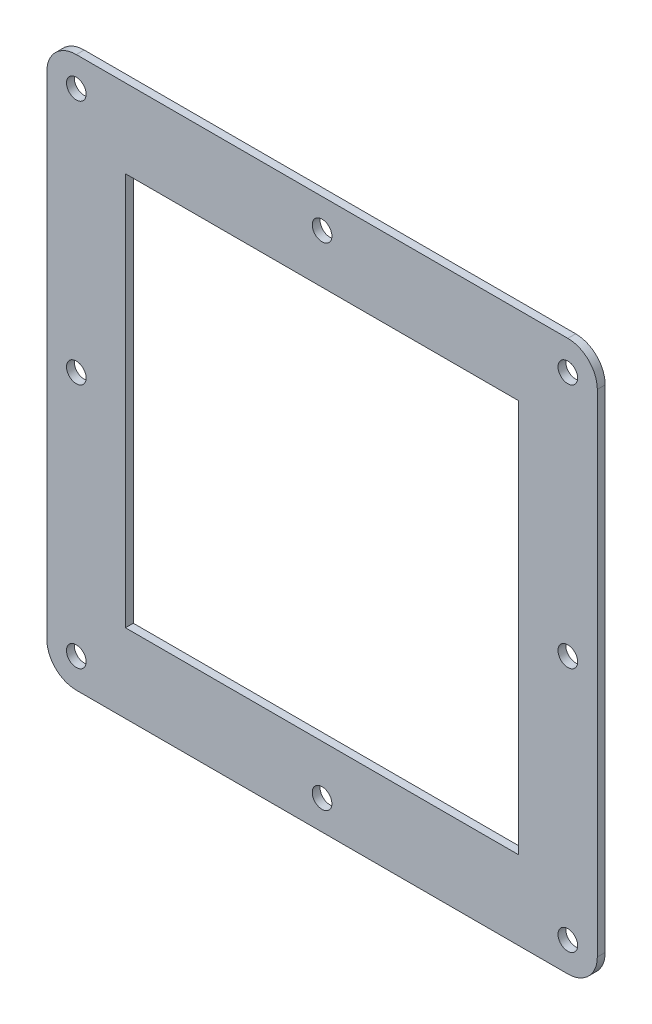
SolidWorks part; units mm, degrees
ref_plane "Front Plane" through (0, 0, 0) normal (0, 0, 1) x (1, 0, 0)
ref_plane "Top Plane" through (0, 0, 0) normal (0, 1, 0) x (1, 0, 0)
ref_plane "Right Plane" through (0, 0, 0) normal (1, 0, 0) x (0, 0, -1)
sketch "Sketch2" plane through (0, 0, 0) normal (0, 0, 1) x (1, 0, 0)
  line L0 (-125, 125) -> (125, 125) construction
  line L1 (-125, 140) -> (125, 140)
  line L2 (-140, 125) -> (-140, -125)
  line L3 (-125, -140) -> (125, -140)
  line L4 (140, 125) -> (140, -125)
  line L5 (-140, 140) -> (140, -140) construction
  line L6 (-140, -140) -> (140, 140) construction
  line L7 (125, 125) -> (125, -125) construction
  line L8 (125, -125) -> (-125, -125) construction
  line L9 (-125, -125) -> (-125, 125) construction
  arc A0 (-140, -125) -> (-125, -140) centre (-125, -125) ccw
  arc A1 (125, -140) -> (140, -125) centre (125, -125) ccw
  arc A2 (125, 140) -> (140, 125) centre (125, 125) cw
  arc A3 (-125, 140) -> (-140, 125) centre (-125, 125) ccw
  circle A4 centre (-125, 125) radius 5
  circle A5 centre (0, 125) radius 5
  circle A6 centre (125, 125) radius 5
  circle A13 centre (0, 0) radius 4
  circle A14 centre (125, 0) radius 5
  circle A15 centre (-125, 0) radius 5
  circle A16 centre (-125, -125) radius 5
  circle A17 centre (0, -125) radius 5
  circle A18 centre (125, -125) radius 5
  point P0 (0, 0)
  dimension "D3" = 15
  dimension "D4" = 10
  dimension "D5" = 10
  dimension "D6" = 10
  dimension "D7" = 8
  dimension "D8" = 10
  dimension "D9" = 10
  dimension "D10" = 10
  dimension "D11" = 10
  dimension "D1" = 280
  dimension "D2" = 280
extrude "Boss-Extrude1" add sketch "Sketch2" along normal blind 4
sketch "Sketch3" plane through (0, 0, 4) normal (0, 0, 1) x (1, 0, 0)
  line L1 (-100, 100) -> (100, 100)
  line L2 (-100, 100) -> (-100, -100)
  line L3 (-100, -100) -> (100, -100)
  line L4 (100, 100) -> (100, -100)
  line L5 (-100, 100) -> (100, -100) construction
  line L6 (-100, -100) -> (100, 100) construction
  point P0 (0, 0)
  dimension "D1" = 200
  dimension "D2" = 200
extrude "Cut-Extrude1" cut sketch "Sketch3" against normal blind 10
